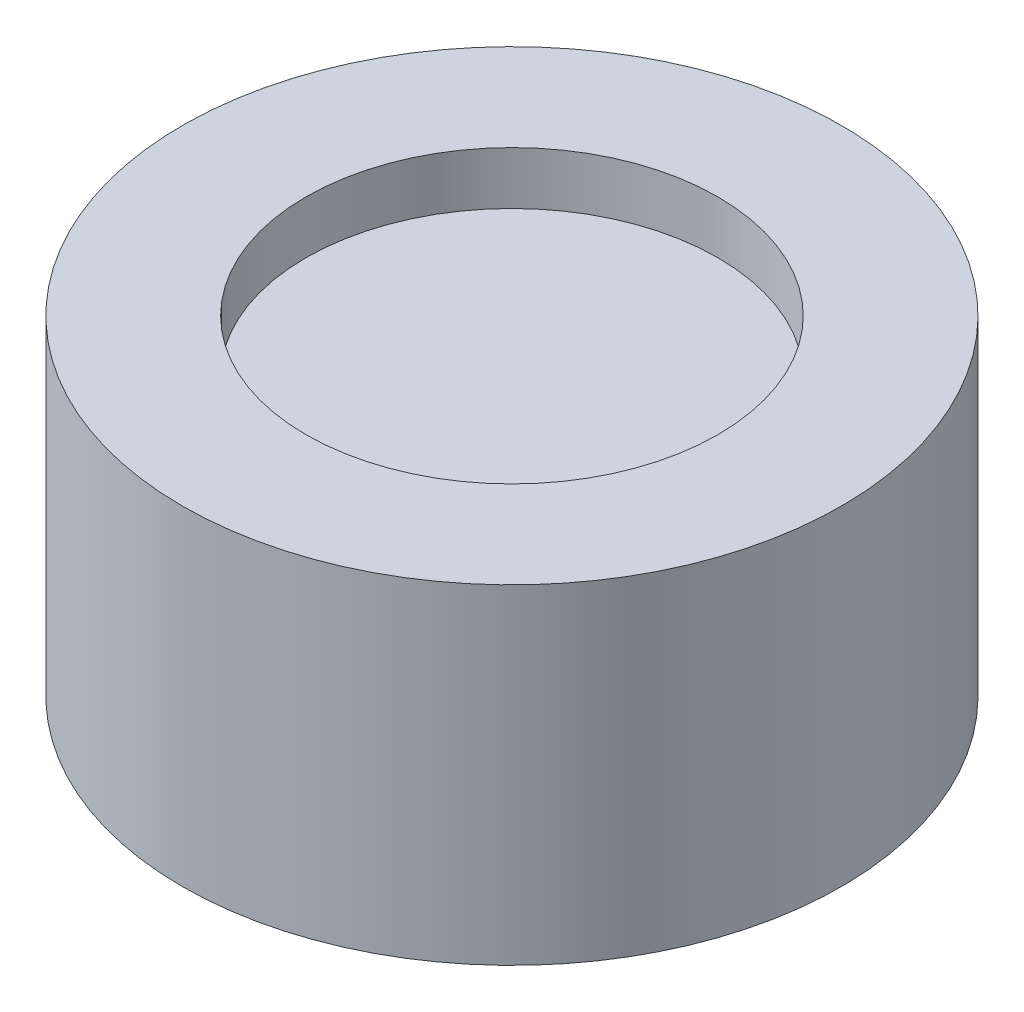
SolidWorks part; units mm, degrees
material "1060 Alloy"
ref_plane "Front Plane" through (0, 0, 0) normal (0, 0, 1) x (1, 0, 0)
ref_plane "Top Plane" through (0, 0, 0) normal (0, 1, 0) x (1, 0, 0)
ref_plane "Right Plane" through (0, 0, 0) normal (1, 0, 0) x (0, 0, -1)
sketch "Sketch1" plane through (0, 0, 0) normal (0, 1, 0) x (1, 0, 0)
  circle A0 centre (0, 0) radius 6.35
  dimension "D1" = 12.7
extrude "Boss-Extrude1" add sketch "Sketch1" along normal blind 6.35
sketch "Sketch2" plane through (0, 6.35, 0) normal (0, 1, 0) x (1, 0, 0)
  circle A0 centre (0, 0) radius 3.9688
  dimension "D1" = 7.9375
extrude "Cut-Extrude1" cut sketch "Sketch2" against normal blind 1.016
hole_wizard "#4-40 Tapped Hole1" positions "Sketch4" profile "Sketch3" tap size "#4-40" standard "ANSI Inch"
sketch "Sketch4" plane through (0, 0, 0) normal (0, -1, 0) x (-1, 0, 0)
  point P0 (0, 0)
sketch "Sketch3" plane through (0, 0, 0) normal (1, 0, 0) x (0, 0, -1)
  line L0 (0, 0) -> (0, 2.7112)
  line L1 (0, 2.7112) -> (1.1303, 2.032)
  line L2 (1.1303, 2.032) -> (1.1303, 0)
  line L5 (1.1303, 0) -> (0, 0)
  line L10 (0, 2.7112) -> (-1.1303, 2.032) construction
  line L11 (0, -6.35) -> (0, 107.95) construction
  dimension "Tap Drill Dia." = 2.2606
  dimension "Tap Drill Depth" = 2.032
  dimension "Drill Angle" = 118
cosmetic thread "Hole Thread1" parameters "D1"=2.032, "D2"=2.8448
